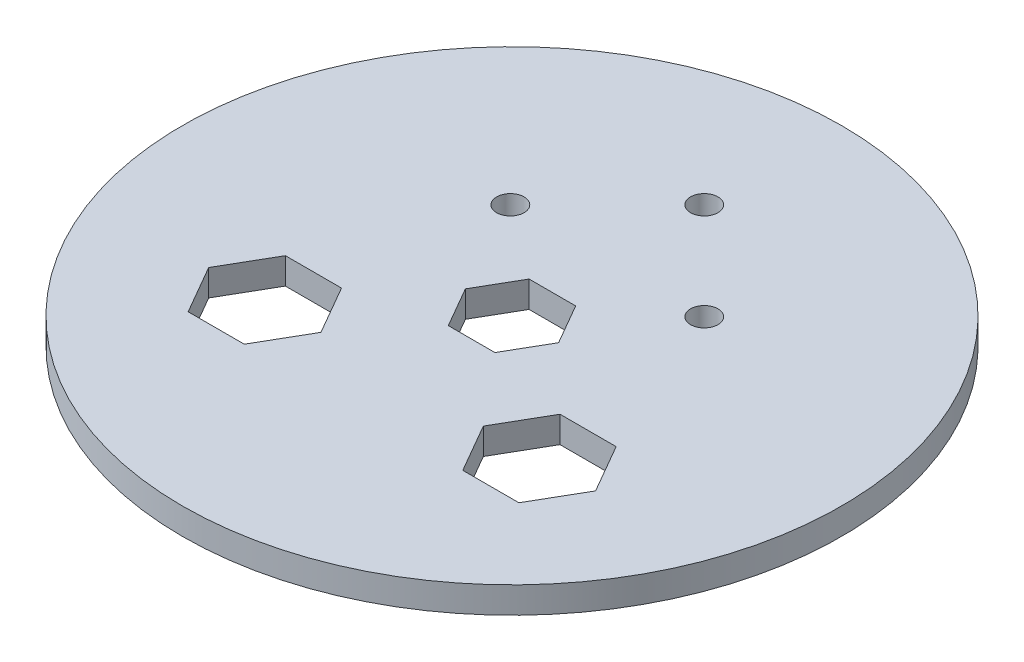
SolidWorks part; units mm, degrees
ref_plane "Front Plane" through (0, 0, 0) normal (0, 0, 1) x (1, 0, 0)
ref_plane "Top Plane" through (0, 0, 0) normal (0, 1, 0) x (1, 0, 0)
ref_plane "Right Plane" through (0, 0, 0) normal (1, 0, 0) x (0, 0, -1)
sketch "Sketch1" plane through (0, 0, 0) normal (0, 1, 0) x (1, 0, 0)
  line L0 (-25, -20) -> (25, -20) construction
  line L1 (8.487, 0) -> (4.2435, 7.35)
  line L2 (4.2435, 7.35) -> (-4.2435, 7.35)
  line L3 (-4.2435, 7.35) -> (-8.487, 0)
  line L4 (-8.487, 0) -> (-4.2435, -7.35)
  line L5 (-4.2435, -7.35) -> (4.2435, -7.35)
  line L6 (4.2435, -7.35) -> (8.487, 0)
  line L7 (-14.7809, -20) -> (-19.8905, -11.15)
  line L8 (-19.8905, -11.15) -> (-30.1095, -11.15)
  line L9 (-30.1095, -11.15) -> (-35.2191, -20)
  line L10 (-35.2191, -20) -> (-30.1095, -28.85)
  line L11 (-30.1095, -28.85) -> (-19.8905, -28.85)
  line L12 (-19.8905, -28.85) -> (-14.7809, -20)
  line L13 (35.2191, -20) -> (30.1095, -11.15)
  line L14 (30.1095, -11.15) -> (19.8905, -11.15)
  line L15 (19.8905, -11.15) -> (14.7809, -20)
  line L16 (14.7809, -20) -> (19.8905, -28.85)
  line L17 (19.8905, -28.85) -> (30.1095, -28.85)
  line L18 (30.1095, -28.85) -> (35.2191, -20)
  circle A0 centre (0, 0) radius 60
  circle A1 centre (0, 0) radius 7.35 construction
  circle A2 centre (-25, -20) radius 8.85 construction
  circle A3 centre (25, -20) radius 8.85 construction
  point P19 (0, -20)
  point P27 (-15.806, -11.15)
  dimension "D1" = 120
  dimension "D2" = 14.7
  dimension "D3" = 17.7
  dimension "D4" = 20
  dimension "D5" = 50
extrude "Boss-Extrude1" add sketch "Sketch1" along normal mid plane 4.8
sketch "Sketch2" plane through (0, 2.4, 0) normal (0, 1, 0) x (1, 0, 0)
  circle A0 centre (-17.65, 17.35) radius 2.25 construction
  circle A1 centre (17.65, 17.35) radius 2.25 construction
  circle A2 centre (0, 35) radius 2.25 construction
  circle A3 centre (-17.65, 17.35) radius 2.25 construction
  circle A4 centre (17.65, 17.35) radius 2.25 construction
  circle A5 centre (0, 35) radius 2.25 construction
  circle A7 centre (0, 35) radius 2.5
  circle A8 centre (17.65, 17.35) radius 2.5
  circle A10 centre (-17.65, 17.35) radius 2.5
  dimension "D1" = 0.25
extrude "Cut-Extrude1" cut sketch "Sketch2" against normal through all
